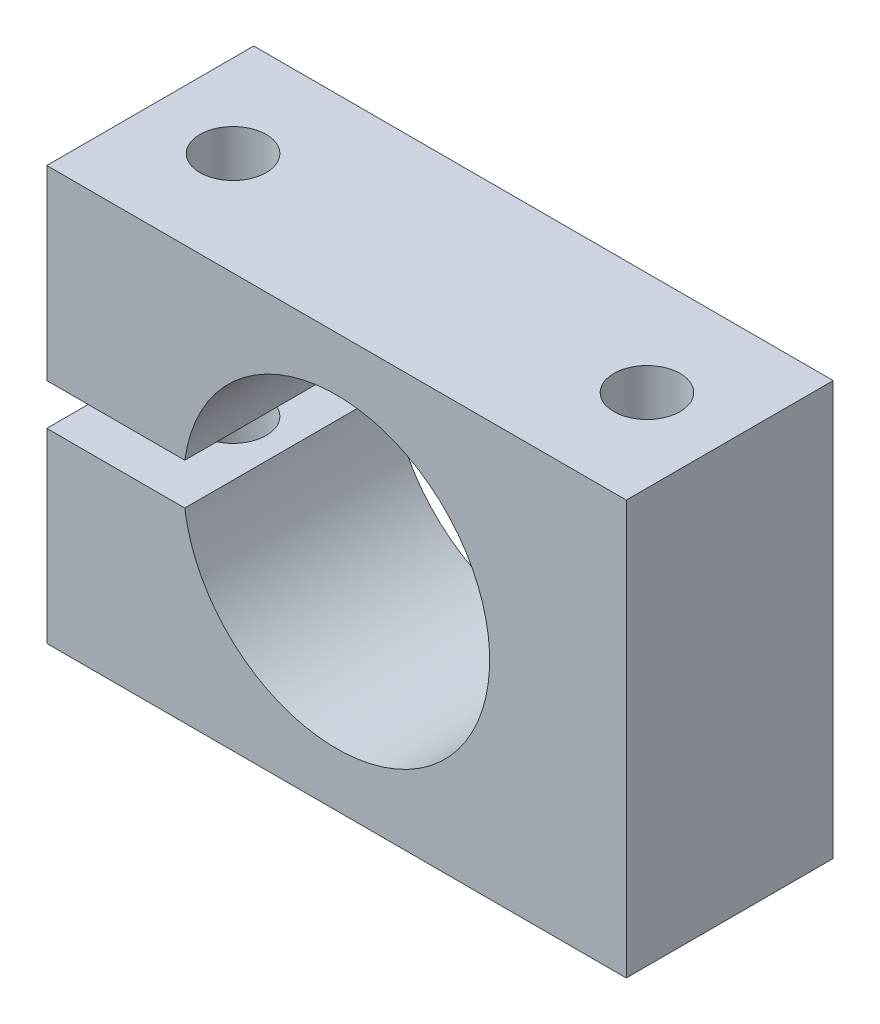
SolidWorks part; units mm, degrees
material "Kiefer"
ref_plane "Ebene vorne" through (0, 0, 0) normal (0, 0, 1) x (1, 0, 0)
ref_plane "Ebene oben" through (0, 0, 0) normal (0, 1, 0) x (1, 0, 0)
ref_plane "Ebene rechts" through (0, 0, 0) normal (1, 0, 0) x (0, 0, -1)
sketch "Skizze1" plane through (0, 0, 0) normal (0, 1, 0) x (1, 0, 0)
  line L1 (-35, 12.5) -> (35, 12.5)
  line L2 (-35, 12.5) -> (-35, -12.5)
  line L3 (-35, -12.5) -> (35, -12.5)
  line L4 (35, 12.5) -> (35, -12.5)
  line L5 (-35, 12.5) -> (35, -12.5) construction
  line L6 (-35, -12.5) -> (35, 12.5) construction
  point P0 (0, 0)
  dimension "D1" = 70
  dimension "D2" = 25
extrude "Aufsatz-Linear austragen1" add sketch "Skizze1" along normal blind 50
sketch "Skizze2" plane through (0, 0, 12.5) normal (0, 0, 1) x (1, 0, 0)
  line L0 (0, 0) -> (0, 50) construction
  line L1 (-35, 50) -> (35, 50) construction
  line L2 (0, 25) -> (-35, 25) construction
  line L3 (-35, 50) -> (-35, 0) construction
  line L5 (-35, 27.5) -> (0, 27.5)
  line L6 (-35, 27.5) -> (-35, 22.5)
  line L7 (-35, 22.5) -> (0, 22.5)
  line L8 (0, 27.5) -> (0, 22.5)
  line L9 (-35, 27.5) -> (0, 22.5) construction
  line L10 (-35, 22.5) -> (0, 27.5) construction
  circle A0 centre (0, 25) radius 18.5
  point P7 (-17.5, 25)
  line M6 (-35, 50) -> (-35, 0)
  dimension "D1" = 37
  dimension "D2" = 5
extrude "Schnitt-Linear austragen1" cut sketch "Skizze2" against normal blind 50 contours L7 A0 L5 L8 | L5 A0 L7 L8 | A0 L5 L7 M6
sketch "Skizze3" plane through (0, 0, 0) normal (0, -1, 0) x (1, 0, 0)
  line L0 (-25, 0) -> (25, 0) construction
  circle A0 centre (-25, 0) radius 4
  circle A1 centre (25, 0) radius 4
  point P2 (0, 0)
  dimension "D2" = 8
  dimension "D1" = 50
extrude "Schnitt-Linear austragen2" cut sketch "Skizze3" against normal through all
